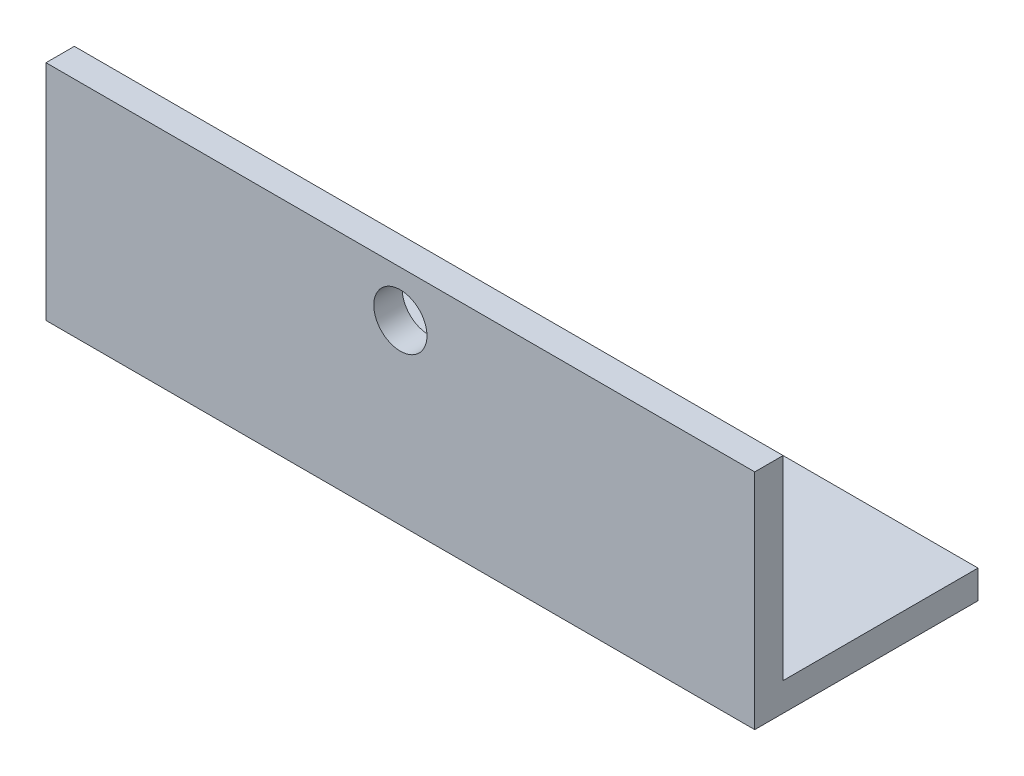
SolidWorks part; units mm, degrees
ref_plane "Front Plane" through (0, 0, 0) normal (0, 0, 1) x (1, 0, 0)
ref_plane "Top Plane" through (0, 0, 0) normal (0, 1, 0) x (1, 0, 0)
ref_plane "Right Plane" through (0, 0, 0) normal (1, 0, 0) x (0, 0, -1)
sketch "Sketch1" plane through (0, 0, 0) normal (0, 1, 0) x (1, 0, 0)
  line L0 (-20, 6.3) -> (20, 6.3) construction
  line L1 (-20, 12.6) -> (20, 12.6)
  line L2 (-20, 12.6) -> (-20, 0)
  line L3 (-20, 0) -> (20, 0)
  line L4 (20, 12.6) -> (20, 0)
  line L5 (0, 12.6) -> (0, 0)
  circle A0 centre (-12.5, 6.3) radius 1.5
  circle A1 centre (12.5, 6.3) radius 1.5
  point P4 (0, 0)
  dimension "D3" = 3
  dimension "D1" = 12.6
  dimension "D2" = 40
  dimension "D4" = 7.5
extrude "Boss-Extrude1" add sketch "Sketch1" along normal blind 1.6 contours L0 L2 L3 L5 A0 | L0 L5 L3 L4 A1 | L5 L0 A1 L4 L1 | L2 L0 A0 L5 L1
sketch "Sketch3" plane through (0, 1.6, 0) normal (0, 1, 0) x (1, 0, 0)
  line L0 (-20, 0) -> (20, 0) construction
  line L1 (-20, 0) -> (20, 0)
  line L2 (-20, 0) -> (-20, 1.6)
  line L3 (-20, 1.6) -> (20, 1.6)
  line L4 (20, 0) -> (20, 1.6)
  line L5 (-20, 12.6) -> (-20, 0) construction
  line L6 (20, 12.6) -> (20, 0) construction
  dimension "D1" = 1.6
extrude "Boss-Extrude3" add sketch "Sketch3" along normal blind 11
sketch "Sketch4" plane through (0, 0, 0) normal (0, 0, 1) x (1, 0, 0)
  line L0 (0, 0) -> (0, 12.6) construction
  line L1 (-20, 12.6) -> (20, 12.6) construction
  line L2 (-20, 0) -> (20, 0) construction
  circle A0 centre (0, 10) radius 1.5
  point P7 (0, 0)
  dimension "D2" = 3
  dimension "D1" = 10
extrude "Cut-Extrude2" cut sketch "Sketch4" against normal through all
